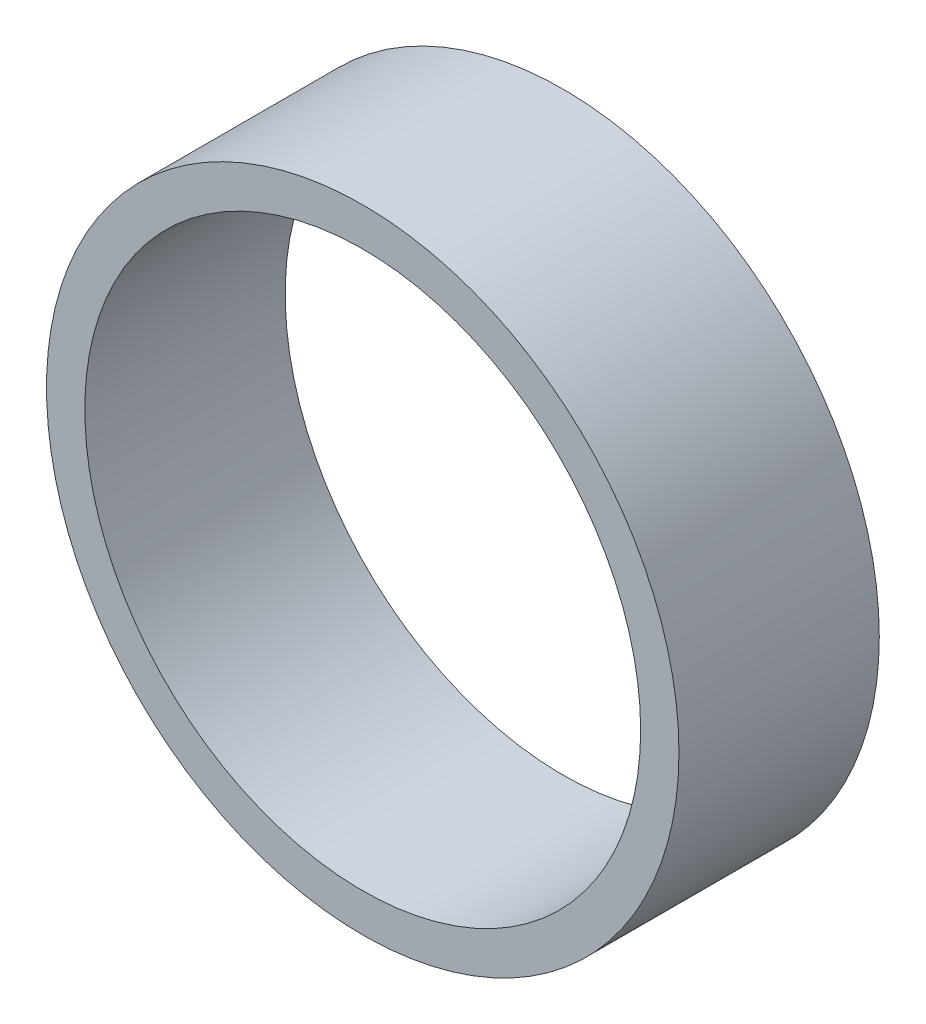
SolidWorks part; units mm, degrees
ref_plane "Front Plane" through (0, 0, 0) normal (0, 0, 1) x (1, 0, 0)
ref_plane "Top Plane" through (0, 0, 0) normal (0, 1, 0) x (1, 0, 0)
ref_plane "Right Plane" through (0, 0, 0) normal (1, 0, 0) x (0, 0, -1)
sketch "Sketch1" plane through (0, 0, 0) normal (0, 0, 1) x (1, 0, 0)
  circle A0 centre (10.7646, -2.1892) radius 10.985
  circle A1 centre (10.7646, -2.1892) radius 3.965
  dimension "D1" = 21.97
  dimension "D2" = 7.93
extrude "Boss-Extrude1" add sketch "Sketch1" along normal blind 6.96
sketch "Sketch2" plane through (0, 0, 6.96) normal (0, 0, 1) x (1, 0, 0)
  line L0 (6.7996, -2.1892) -> (10.7646, -2.1892)
  circle A0 centre (10.7646, -2.1892) radius 3.965 construction
  circle A1 centre (10.7646, -2.1892) radius 9.655
  circle M2 centre (10.7646, -2.1892) radius 3.965
  dimension "D1" = 19.31
extrude "Cut-Extrude1" cut sketch "Sketch2" against normal blind 6.96 contours A1 M2
